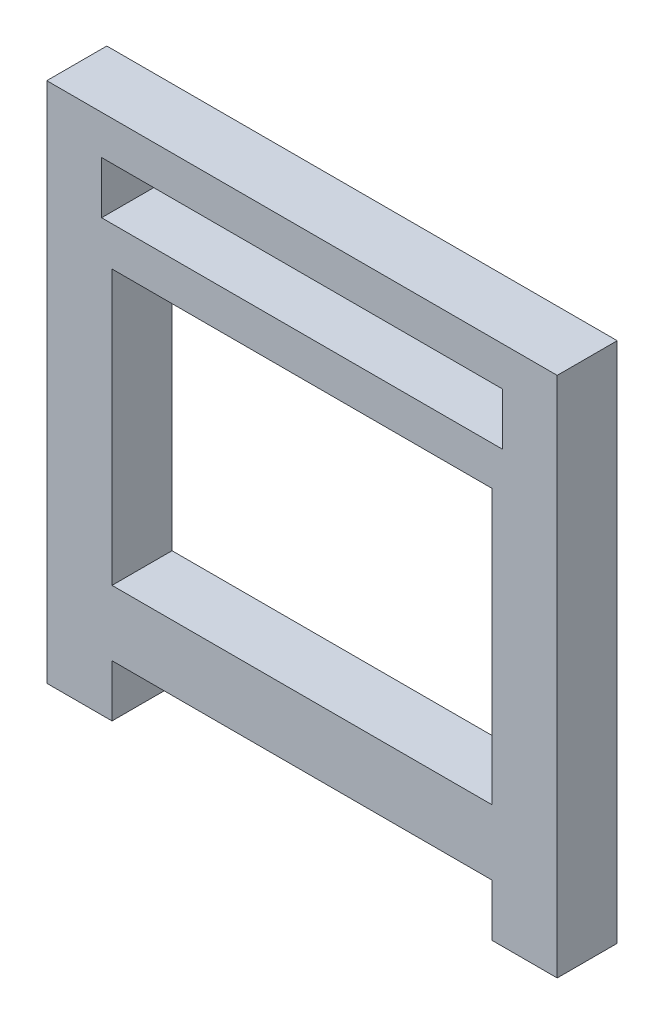
SolidWorks part; units mm, degrees
ref_plane "Front Plane" through (0, 0, 0) normal (0, 0, 1) x (1, 0, 0)
ref_plane "Top Plane" through (0, 0, 0) normal (0, 1, 0) x (1, 0, 0)
ref_plane "Right Plane" through (0, 0, 0) normal (1, 0, 0) x (0, 0, -1)
sketch "Sketch1" plane through (0, 0, 0) normal (0, 0, 1) x (1, 0, 0)
  line L0 (0, 0) -> (0, -2)
  line L1 (2.5, 0) -> (17.06, 0)
  line L2 (0, 0) -> (0, 18)
  line L3 (0, 18) -> (19.56, 18)
  line L4 (19.56, 0) -> (19.56, 18)
  line L5 (0, -2) -> (2.5, -2)
  line L6 (2.5, -2) -> (2.5, 0)
  line L7 (19.56, 0) -> (19.56, -2)
  line L8 (19.56, -2) -> (17.06, -2)
  line L9 (17.06, -2) -> (17.06, 0)
  line L12 (2.5, 2.5) -> (17.06, 2.5)
  line L13 (2.5, 2.5) -> (2.5, 13)
  line L14 (2.5, 13) -> (17.06, 13)
  line L15 (17.06, 2.5) -> (17.06, 13)
  line L16 (2.1, 14.5) -> (17.46, 14.5)
  line L17 (2.1, 14.5) -> (2.1, 16.5)
  line L18 (2.1, 16.5) -> (17.46, 16.5)
  line L19 (17.46, 14.5) -> (17.46, 16.5)
  dimension "D1" = 18
  dimension "D2" = 2.1
  dimension "D3" = 14.56
  dimension "D4" = 2
  dimension "D5" = 2
  dimension "D6" = 2.1
  dimension "D7" = 2.5
  dimension "D8" = 10.5
  dimension "D9" = 2
  dimension "D10" = 1.5
  dimension "D11" = 2.5
  dimension "D12" = 2.5
extrude "Boss-Extrude1" add sketch "Sketch1" along normal blind 2.3
